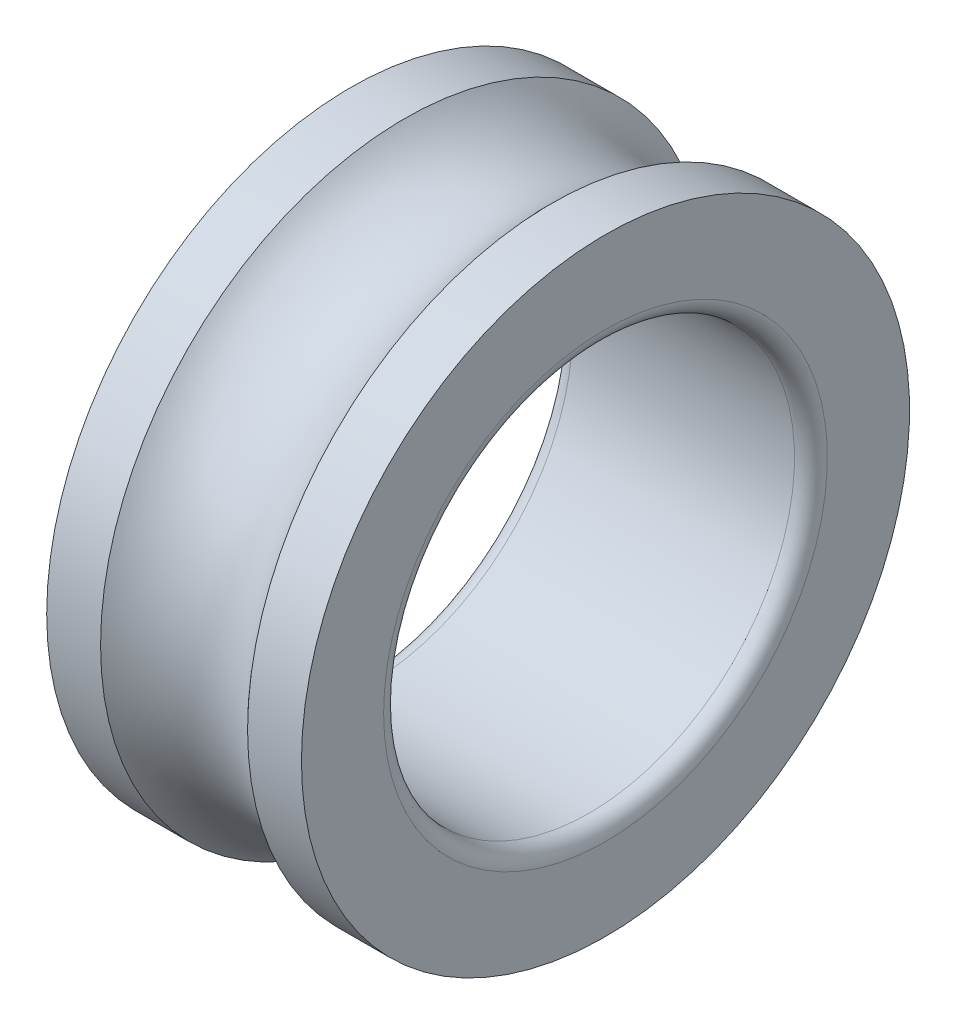
SolidWorks part; units mm, degrees
ref_plane "前视基准面" through (0, 0, 0) normal (0, 0, 1) x (1, 0, 0)
ref_plane "上视基准面" through (0, 0, 0) normal (0, 1, 0) x (1, 0, 0)
ref_plane "右视基准面" through (0, 0, 0) normal (1, 0, 0) x (0, 0, -1)
sketch "草图1" plane through (0, 0, 0) normal (0, 0, 1) x (1, 0, 0)
  line L0 (0, 0) -> (0, 31) construction
  line L1 (0, 0) -> (22.5451, 0) construction
  line L2 (8.9443, 37) -> (15.5, 37)
  line L3 (-15.5, 37) -> (-8.9443, 37)
  line L4 (-15.5, 37) -> (-15.5, 25)
  line L5 (-15.5, 25) -> (15.5, 25)
  line L6 (15.5, 37) -> (15.5, 25)
  line L7 (-15.5, 37) -> (15.5, 25) construction
  line L8 (-15.5, 25) -> (15.5, 37) construction
  arc A0 (-8.9443, 37) -> (8.9443, 37) centre (0, 45) ccw
  point P11 (0, 25)
  point P12 (0, 0)
  point P14 (-0.5163, 44.941)
  point P15 (-4.7005, 55.0057)
  dimension "D1" = 12
  dimension "D2" = 31
  dimension "D3" = 25
  dimension "D4" = 37
  dimension "D5" = 8
revolve "旋转1" add sketch "草图1" angle 360 about L1
fillet "圆角1" radius 2 2 edges at (-15.5, 0, 25) (15.5, 0, 25)
